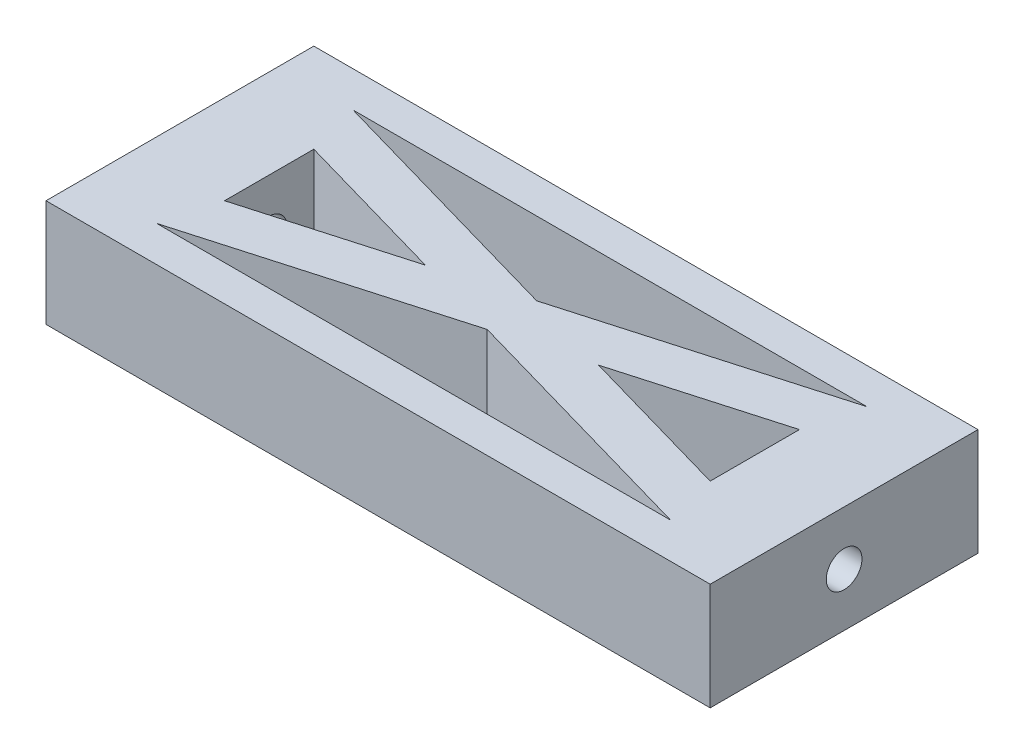
SolidWorks part; units mm, degrees
material "PLA"
ref_plane "Front" through (0, 0, 0) normal (0, 0, 1) x (1, 0, 0)
ref_plane "Top" through (0, 0, 0) normal (0, 1, 0) x (1, 0, 0)
ref_plane "Right" through (0, 0, 0) normal (1, 0, 0) x (0, 0, -1)
sketch "Sketch1" plane through (0, 0, 0) normal (0, 1, 0) x (1, 0, 0)
  line L1 (23.622, -9.525) -> (-23.622, -9.525)
  line L2 (23.622, -9.525) -> (23.622, 9.525)
  line L3 (23.622, 9.525) -> (-23.622, 9.525)
  line L4 (-23.622, -9.525) -> (-23.622, 9.525)
  line L5 (23.622, -9.525) -> (-23.622, 9.525) construction
  line L6 (23.622, 9.525) -> (-23.622, -9.525) construction
  point P0 (0, 0)
  dimension "D1" = 19.05
  dimension "D2" = 47.244
extrude "Boss-Extrude1" add sketch "Sketch1" along normal blind 7.62
sketch "Sketch2" plane through (0, 7.62, 0) normal (0, 1, 0) x (1, 0, 0)
  line L0 (-17.272, -3.175) -> (-17.272, 6.985)
  line L1 (-17.272, 6.985) -> (18.264, 6.985)
  line L2 (18.264, 6.985) -> (-17.272, -3.175)
  line L3 (23.622, 9.525) -> (-23.622, 9.525) construction
  line L4 (-23.622, 9.525) -> (-23.622, -9.525) construction
  line L5 (-17.272, 3.175) -> (-17.272, -6.985)
  line L6 (-17.272, -6.985) -> (18.264, -6.985)
  line L7 (18.264, -6.985) -> (-17.272, 3.175)
  line L8 (-23.622, -9.525) -> (23.622, -9.525) construction
  line L9 (-18.288, 6.985) -> (17.272, 6.985)
  line L10 (17.272, 6.985) -> (17.272, -3.175)
  line L11 (17.272, -3.175) -> (-18.288, 6.985)
  line L12 (23.622, -9.525) -> (23.622, 9.525) construction
  line L13 (17.272, 3.175) -> (17.272, -6.985)
  line L14 (17.272, -6.985) -> (-18.288, -6.985)
  line L15 (-18.288, -6.985) -> (17.272, 3.175)
  dimension "D1" = 10.16
  dimension "D2" = 2.54
  dimension "D3" = 6.35
  dimension "D4" = 35.536
  dimension "D5" = 35.536
  dimension "D6" = 2.54
  dimension "D7" = 10.16
  dimension "D8" = 35.56
  dimension "D9" = 6.35
  dimension "D10" = 10.16
  dimension "D11" = 35.56
  dimension "D12" = 10.16
sketch "Sketch4" plane through (23.622, 0, 0) normal (1, 0, 0) x (0, 0, -1)
  line L0 (0, 55) -> (0, -55) construction
  line L1 (55, 0) -> (-55, 0) construction
  circle A0 centre (0, 3.7869) radius 1.27
  dimension "D1" = 2.54
  dimension "D2" = 3.7869
extrude "Cut-Extrude3" cut sketch "Sketch4" against normal blind 7.62
sketch "Sketch5" plane through (-23.622, 0, 0) normal (-1, 0, 0) x (0, 0, 1)
  line L0 (0, -55) -> (0, 55) construction
  line L1 (55, 0) -> (-55, 0) construction
  circle A0 centre (0, 3.81) radius 1.27
  dimension "D1" = 2.54
  dimension "D2" = 3.81
extrude "Cut-Extrude4" cut sketch "Sketch5" against normal blind 7.62
extrude "Cut-Extrude8" cut sketch "Sketch2" against normal through all contours L2 L7 L0 | L15 L11 L10 | L11 L2 L10 L1 L0 | L15 L5 L6 L13 L7 | L7 L13 L6 | L15 L14 L5 | L11 L0 L9 | L1 L10 L2
